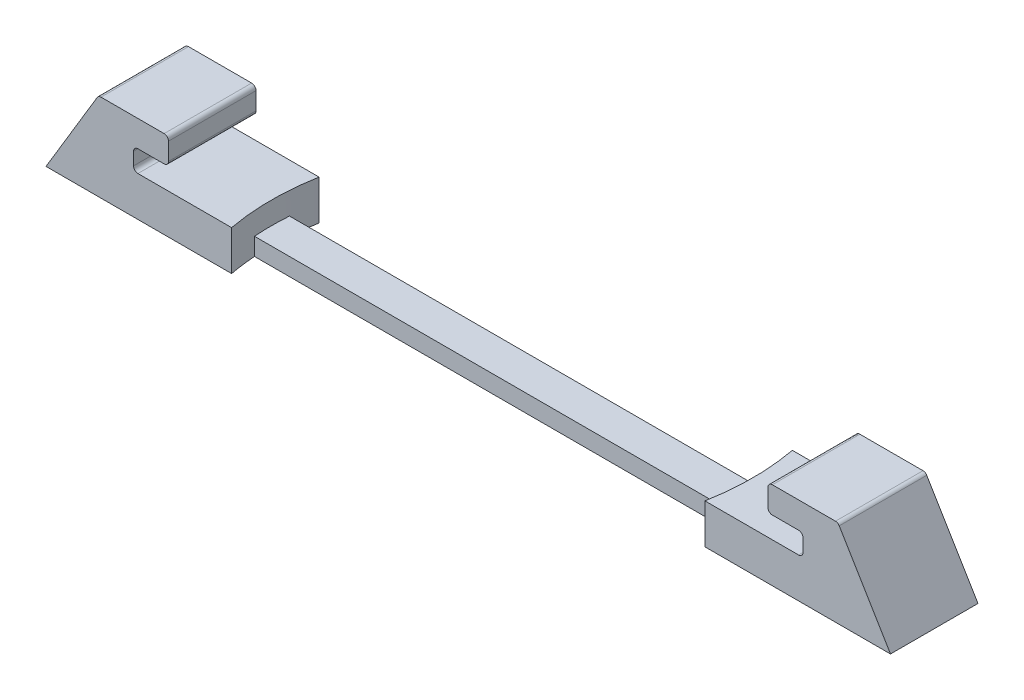
SolidWorks part; units mm, degrees
ref_plane "Front Plane" through (0, 0, 0) normal (0, 0, 1) x (1, 0, 0)
ref_plane "Top Plane" through (0, 0, 0) normal (0, 1, 0) x (1, 0, 0)
ref_plane "Right Plane" through (0, 0, 0) normal (1, 0, 0) x (0, 0, -1)
sketch "Sketch1" plane through (0, 0, 0) normal (0, 0, 1) x (1, 0, 0)
  line L0 (0, 0) -> (0, 2.3) construction
  line L1 (0, 0) -> (-76.2, 0) construction
  line L2 (-76.2, 0) -> (-76.2, 2.3) construction
  line L3 (-76.35, 1.95) -> (-76.35, 0.5)
  line L4 (-76.2, 2.3) -> (-76.35, 2.3) construction
  line L5 (-76.2, 2.3) -> (-76.2, 2.45) construction
  line L6 (-76.2, 2.45) -> (-76.35, 2.45) construction
  line L7 (-76.35, 2.3) -> (-76.35, 2.45) construction
  line L8 (-75.85, 2.45) -> (-72.85, 2.45)
  line L9 (-72.35, 2.95) -> (-72.35, 4.95)
  line L10 (-72.85, 5.45) -> (-79.85, 5.45)
  line L12 (-79.85, -4.55) -> (3.65, -4.55)
  line L13 (-38.1, -9.7056) -> (-38.1, 9.7056) construction
  line L14 (-38.1, -4.55) -> (-38.1, 0)
  line L15 (-75.85, 0) -> (-0.35, 0)
  line L16 (-79.85, 5.45) -> (-80.0669, 5.45)
  line L17 (-80.35, 5.45) -> (-80.35, -4.55) construction
  line L18 (-80.35, -4.55) -> (-86.35, -4.55)
  line L19 (-86.35, -4.55) -> (-80.4957, 5.2072)
  line L20 (-79.85, -4.55) -> (-80.35, -4.55)
  line L21 (4.15, 5.45) -> (4.15, -4.55) construction
  line L22 (0.15, 2.3) -> (0.15, 2.45) construction
  line L23 (0, 2.45) -> (0.15, 2.45) construction
  line L24 (0, 2.3) -> (0, 2.45) construction
  line L25 (0, 2.3) -> (0.15, 2.3) construction
  line L26 (0, 0) -> (0, 2.3) construction
  line L27 (3.65, -4.55) -> (4.15, -4.55)
  line L28 (10.15, -4.55) -> (4.2957, 5.2072)
  line L29 (4.15, -4.55) -> (10.15, -4.55)
  line L30 (3.65, 5.45) -> (3.8669, 5.45)
  line L31 (-3.35, 5.45) -> (3.65, 5.45)
  line L32 (-3.85, 2.95) -> (-3.85, 4.95)
  line L33 (-0.35, 2.45) -> (-3.35, 2.45)
  line L34 (0.15, 1.95) -> (0.15, 0.5)
  arc A0 (-72.35, 4.95) -> (-72.85, 5.45) centre (-72.85, 4.95) ccw
  arc A2 (-72.85, 2.45) -> (-72.35, 2.95) centre (-72.85, 2.95) ccw
  arc A4 (-76.35, 1.95) -> (-75.85, 2.45) centre (-75.85, 1.95) cw
  arc A5 (-76.35, 0.5) -> (-75.85, 0) centre (-75.85, 0.5) ccw
  arc A6 (-80.0669, 5.45) -> (-80.4957, 5.2072) centre (-80.0669, 4.95) ccw
  arc A7 (3.8669, 5.45) -> (4.2957, 5.2072) centre (3.8669, 4.95) cw
  arc A8 (0.15, 0.5) -> (-0.35, 0) centre (-0.35, 0.5) cw
  arc A9 (0.15, 1.95) -> (-0.35, 2.45) centre (-0.35, 1.95) ccw
  arc A10 (-3.35, 2.45) -> (-3.85, 2.95) centre (-3.35, 2.95) cw
  arc A11 (-3.85, 4.95) -> (-3.35, 5.45) centre (-3.35, 4.95) cw
  point P16 (-38.1, 0)
  point P21 (-72.35, 5.45)
  point P24 (-80.35, -4.55)
  point P27 (-72.35, 2.45)
  point P30 (-80.35, 5.45)
  point P60 (4.15, 5.45)
  point P61 (-3.85, 2.45)
  point P62 (4.15, -4.55)
  point P63 (-3.85, 5.45)
  dimension "D10" = 0.5
  dimension "D11" = 6
  dimension "D12" = 0.5
  dimension "D13" = 0.5
  dimension "D14" = 0.5
  dimension "D1" = 76.2
  dimension "D2" = 2.3
  dimension "D4" = 0.15
  dimension "D5" = 0.15
  dimension "D6" = 4
  dimension "D7" = 8
  dimension "D8" = 10
  dimension "D9" = 3
extrude "Boss-Extrude1" add sketch "Sketch1" along normal blind 180 contours L16 A6 L19 L18 L20 L12 L14 L15 A5 L3 A4 L8 A2 L9 A0 L10 | A11 L32 A10 L33 A9 L34 A8 L15 L14 L12 L27 L29 L28 A7 L30 L31
sketch "Sketch2" plane through (0, 0, 180) normal (0, 0, 1) x (1, 0, 0)
  line L0 (-83.62, 0) -> (7.42, 0)
  line L1 (-86.35, -4.55) -> (-80.4957, 5.2072) construction
  line L2 (10.15, -4.55) -> (4.2957, 5.2072) construction
  line L3 (7.42, 0) -> (7.42, 5.45)
  line L4 (7.42, 5.45) -> (-83.62, 5.45)
  line L5 (-83.62, 5.45) -> (-83.62, 0)
  point P0 (-83.62, 0)
  point P3 (-38.1, 0)
extrude "Cut-Extrude1" cut sketch "Sketch2" against normal blind 30
sketch "Sketch3" plane through (0, 0, 0) normal (0, 0, -1) x (-1, 0, 0)
  line L0 (83.62, 0) -> (-7.42, 0)
  line L1 (-7.42, 0) -> (-7.42, 5.45)
  line L2 (-7.42, 5.45) -> (83.62, 5.45)
  line L3 (83.62, 5.45) -> (83.62, 0)
  point P3 (38.1, 0)
  point P6 (83.62, 0)
extrude "Cut-Extrude2" cut sketch "Sketch3" against normal blind 30
sketch "Sketch4" plane through (0, 0, 0) normal (0, 1, 0) x (1, 0, 0)
  line L0 (-178.1709, -90) -> (-35.3081, -90) construction
  line L1 (-38.1, -16.526) -> (-38.1, 16.526) construction
  line L2 (-86.35, 0) -> (-61.35, 0) construction
  line L3 (-83.62, 0) -> (7.42, 0) construction
  line L4 (-61.35, 0) -> (-61.35, -20) construction
  line L5 (-61.35, -20) -> (-61.35, -10) construction
  line L6 (-61.35, -10) -> (-75.35, -10) construction
  line L7 (-14.85, 0) -> (-14.85, -20) construction
  line L8 (10.15, 0) -> (-14.85, 0) construction
  line L9 (-14.85, -10) -> (-0.85, -10) construction
  line L10 (-14.85, -20) -> (-14.85, -10) construction
  line L11 (10.15, -180) -> (10.15, 0) construction
  line L12 (-83.62, -180) -> (7.42, -180) construction
  line L13 (-50.1, 0) -> (-86.35, 0)
  line L14 (-26.1, 0) -> (10.15, 0)
  line L15 (-50.1, 0) -> (-26.1, 0)
  line L16 (-14.85, -160) -> (-14.85, -170) construction
  line L17 (-14.85, -170) -> (-0.85, -170) construction
  line L18 (10.15, -180) -> (-14.85, -180) construction
  line L24 (-14.85, -180) -> (-14.85, -160) construction
  line L25 (-61.35, -170) -> (-75.35, -170) construction
  line L28 (-48.1, -2) -> (-48.1, -38)
  line L29 (-46.1, -40) -> (-30.1, -40)
  line L30 (-28.1, -38) -> (-28.1, -2)
  line L31 (-61.35, -160) -> (-61.35, -170) construction
  line L32 (-61.35, -180) -> (-61.35, -160) construction
  line L34 (-86.35, -180) -> (-61.35, -180) construction
  line L35 (-28.1, -142) -> (-28.1, -178)
  line L36 (-46.1, -140) -> (-30.1, -140)
  line L37 (-48.1, -178) -> (-48.1, -142)
  line L38 (-50.1, -180) -> (-26.1, -180)
  line L39 (-26.1, -180) -> (10.15, -180)
  line L40 (-50.1, -180) -> (-86.35, -180)
  circle A0 centre (-61.35, -20) radius 4
  circle A1 centre (-75.35, -10) radius 4
  circle A2 centre (-0.85, -10) radius 4
  circle A3 centre (-14.85, -20) radius 4
  circle A8 centre (-38.1, -90) radius 27.5
  arc A15 (-30.1, -40) -> (-28.1, -38) centre (-30.1, -38) ccw
  arc A16 (-48.1, -38) -> (-46.1, -40) centre (-46.1, -38) ccw
  arc A17 (-48.1, -2) -> (-50.1, 0) centre (-50.1, -2) ccw
  arc A18 (-28.1, -2) -> (-26.1, 0) centre (-26.1, -2) cw
  arc A19 (-28.1, -178) -> (-26.1, -180) centre (-26.1, -178) ccw
  arc A20 (-48.1, -178) -> (-50.1, -180) centre (-50.1, -178) cw
  arc A21 (-48.1, -142) -> (-46.1, -140) centre (-46.1, -142) cw
  arc A22 (-30.1, -140) -> (-28.1, -142) centre (-30.1, -142) cw
  circle A27 centre (-14.85, -160) radius 4
  circle A28 centre (-0.85, -170) radius 4
  circle A29 centre (-75.35, -170) radius 4
  circle A30 centre (-61.35, -160) radius 4
  point P3 (-38.1, -90)
  point P6 (-38.1, -90)
  point P27 (-38.1, 0)
  point P32 (-48.1, 0)
  point P36 (-28.1, 0)
  point P71 (-28.1, -180)
  point P72 (-48.1, -180)
  point P73 (-38.1, -180)
  dimension "D1" = 25
  dimension "D3" = 8
  dimension "D6" = 8
  dimension "D7" = 55
  dimension "D8" = 10
  dimension "D9" = 10
  dimension "D10" = 48.25
  dimension "D13" = 2
  dimension "D15" = 2
  dimension "D12" = 2
  dimension "D2" = 20
  dimension "D4" = 10
  dimension "D5" = 14
  dimension "D11" = 90
fillet "Fillet1" radius 1 1 edges at (-79.735, 0, 150)
fillet "Fillet2" radius 1 1 edges at (3.535, 0, 150)
fillet "Fillet3" radius 1 2 edges at (-79.735, 0, 30) (3.535, 0, 30)
extrude "Cut-Extrude3" cut sketch "Sketch4" against normal through all both contours L30 A18 L15 A17 L28 A16 L29 A15 | A1 | A0 | A3 | A2 | A8 | A22 L36 A21 L37 A20 L38 A19 L35 | A30 | A29 | A27 | A28
sketch "Sketch5" plane through (0, 5.45, 0) normal (0, 1, 0) x (1, 0, 0)
  line L0 (-123.1689, -90) -> (-37.8224, -90) construction
  point P3 (-80.4957, -90)
ref_plane "Plane1" through (0, 5.45, 0) normal (0, 1, 0) x (1, 0, 0)
sketch "Sketch6" plane through (0, 5.45, 0) normal (0, 1, 0) x (1, 0, 0)
  line L0 (-38.1, -81.9509) -> (-38.1, -98.0491) construction
  line L1 (-86.35, -180) -> (-86.35, 0) construction
  line L2 (10.15, -95) -> (-86.35, -95)
  line L3 (10.15, -95) -> (10.15, -85)
  line L4 (10.15, -85) -> (-86.35, -85)
  line L5 (-86.35, -95) -> (-86.35, -85)
  line L6 (10.15, -95) -> (-86.35, -85) construction
  line L7 (10.15, -85) -> (-86.35, -95) construction
  line L9 (-86.35, -85) -> (10.15, -85)
  line L10 (-86.35, -85) -> (-86.35, 0)
  line L11 (-86.35, 0) -> (10.15, 0)
  line L12 (10.15, -85) -> (10.15, 0)
  line L13 (-86.35, -95) -> (10.15, -95)
  line L14 (-86.35, -95) -> (-86.35, -180)
  line L15 (-86.35, -180) -> (10.15, -180)
  line L16 (10.15, -95) -> (10.15, -180)
  point P1 (-38.1, -90)
  point P4 (-38.1, -90)
extrude "Cut-Extrude4" cut sketch "Sketch6" against normal through all both contours L16 L2 L14 L15 | L4 L12 L11 L10
ref_plane "Plane2" through (0, -4.55, 0) normal (0, 1, 0) x (1, 0, 0)
sketch "Sketch7" plane through (0, -4.55, 0) normal (0, 1, 0) x (1, 0, 0)
  line L0 (-65.6, -91.9999) -> (-65.6, -87.9999)
  line L1 (-10.6, -91.9999) -> (-10.6, -87.9999)
  line L3 (-65.6, -87.9999) -> (-10.6, -87.9999)
  line L5 (-10.6, -91.9999) -> (-65.6, -91.9999)
  point P3 (-65.6, -89.9999)
  point P6 (-10.6, -89.9999)
  point P8 (-38.1, -90)
  dimension "D1" = 4
  dimension "D2" = 4
extrude "Boss-Extrude3" add sketch "Sketch7" along normal blind 2
